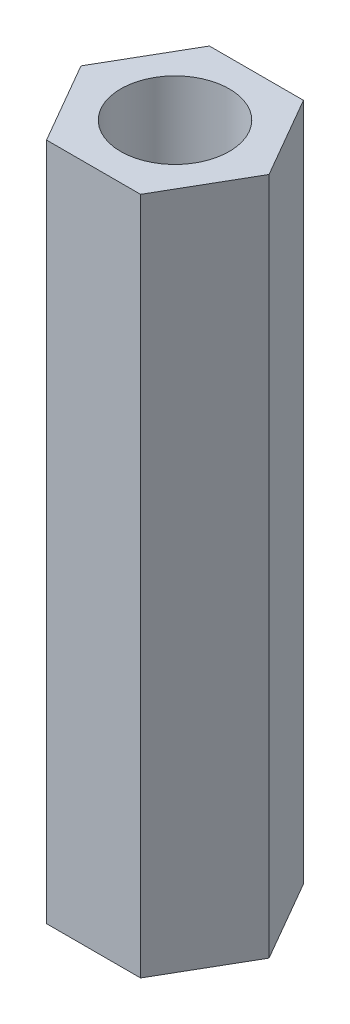
SolidWorks part; units mm, degrees
ref_plane "前视基准面" through (0, 0, 0) normal (0, 0, 1) x (1, 0, 0)
ref_plane "上视基准面" through (0, 0, 0) normal (0, 1, 0) x (1, 0, 0)
ref_plane "右视基准面" through (0, 0, 0) normal (1, 0, 0) x (0, 0, -1)
other "Configuration Table"
sketch "草图1" plane through (0, 0, 0) normal (0, 1, 0) x (1, 0, 0)
  line L1 (-3.4641, 0) -> (-1.7321, -3)
  line L2 (-1.7321, -3) -> (1.7321, -3)
  line L3 (1.7321, -3) -> (3.4641, 0)
  line L4 (3.4641, 0) -> (1.7321, 3)
  line L5 (1.7321, 3) -> (-1.7321, 3)
  line L6 (-1.7321, 3) -> (-3.4641, 0)
  circle A0 centre (0, 0) radius 3 construction
  circle A1 centre (0, 0) radius 2
  dimension "D2" = 4
  dimension "D1" = 6
extrude "凸台-拉伸1" add sketch "草图1" along normal blind 25
